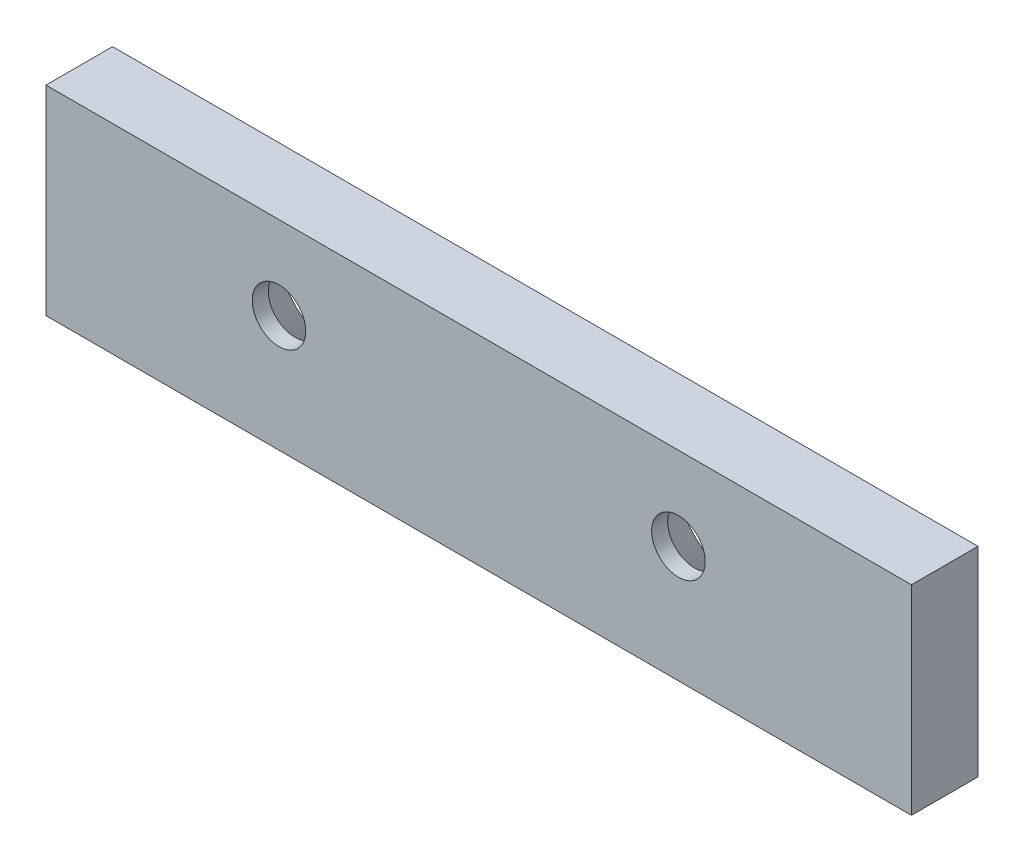
SolidWorks part; units mm, degrees
material "6061 Alloy"
ref_plane "Front Plane" through (0, 0, 0) normal (0, 0, 1) x (1, 0, 0)
ref_plane "Top Plane" through (0, 0, 0) normal (0, 1, 0) x (1, 0, 0)
ref_plane "Right Plane" through (0, 0, 0) normal (1, 0, 0) x (0, 0, -1)
sketch "Sketch1" plane through (0, 0, 0) normal (0, 0, 1) x (1, 0, 0)
  line L1 (0, 0) -> (82.55, 0)
  line L2 (0, 0) -> (0, 19.05)
  line L3 (0, 19.05) -> (82.55, 19.05)
  line L4 (82.55, 0) -> (82.55, 19.05)
  dimension "D1" = 82.55
  dimension "D2" = 19.05
extrude "Boss-Extrude1" add sketch "Sketch1" against normal blind 6.35
hole_wizard "1/4-20 Tapped Hole1" positions "Sketch2" profile "Sketch3" tap size "1/4-20" standard "ANSI Inch" end condition through all
sketch "Sketch2" plane through (0, 0, 0) normal (0, 0, 1) x (1, 0, 0)
  line L0 (82.55, 19.05) -> (0, 19.05) construction
  line L1 (0, 19.05) -> (0, 0) construction
  line L2 (82.55, 0) -> (82.55, 19.05) construction
  point P0 (22.225, 11.1125)
  point P7 (60.325, 11.1125)
  dimension "D1" = 7.9375
  dimension "D2" = 22.225
  dimension "D3" = 7.9375
  dimension "D4" = 22.225
cosmetic thread "Hole Thread1"
cosmetic thread "Hole Thread2"
sketch "Sketch3" plane through (22.225, 11.1125, 0) normal (1, 0, 0) x (0, -1, 0)
  line L0 (0, 0) -> (0, 6.35)
  line L1 (0, 6.35) -> (6.7437, 6.35)
  line L2 (2.5527, 1.5288) -> (2.5527, 0)
  line L5 (2.5527, 0) -> (0, 0)
  line L7 (6.7437, 6.35) -> (2.5527, 1.5288)
  line L8 (-6.7437, 6.35) -> (-2.5527, 1.5288) construction
  line L11 (0, -6.35) -> (0, 107.95) construction
  dimension "Thru Tap Drill Dia." = 5.1054
  dimension "Thru Tap Drill Depth" = 6.35
  dimension "Far C'Sink Dia." = 13.4874
  dimension "Far C'Sink Angle" = 82
